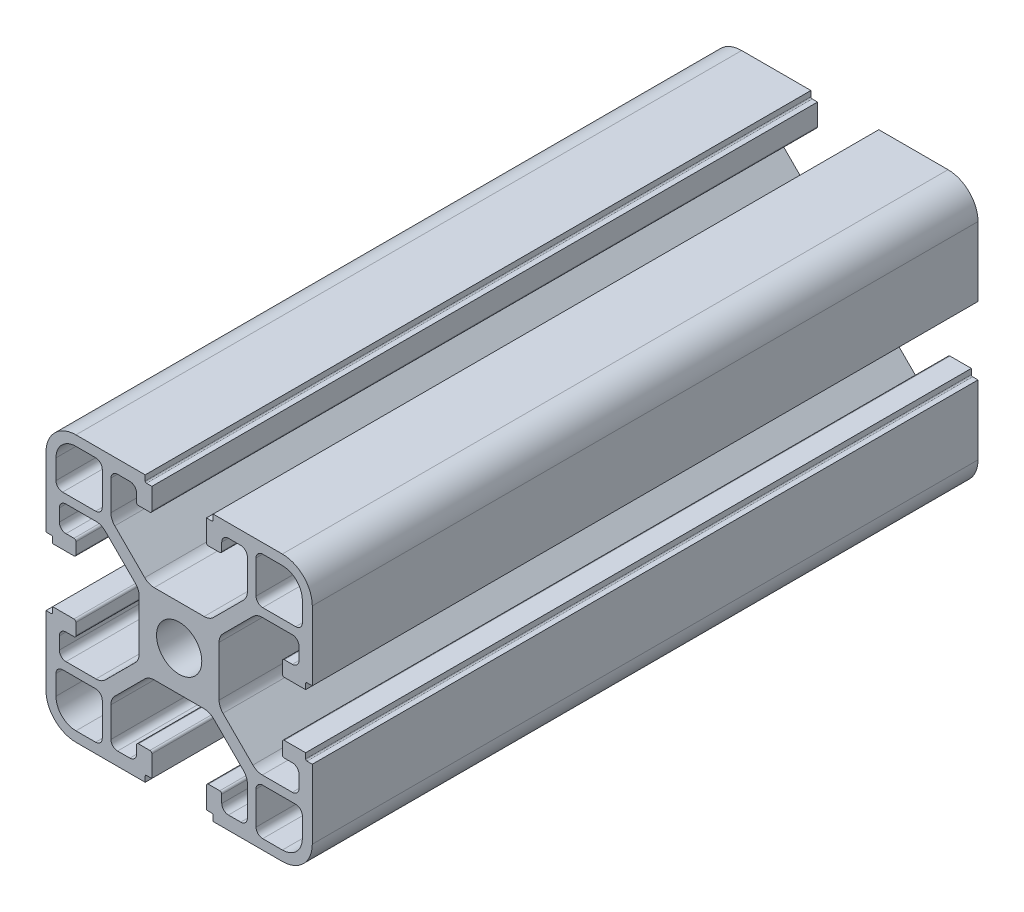
SolidWorks part; units mm, degrees
ref_plane "前视基准面" through (0, 0, 0) normal (0, 0, 1) x (1, 0, 0)
ref_plane "上视基准面" through (0, 0, 0) normal (0, 1, 0) x (1, 0, 0)
ref_plane "右视基准面" through (0, 0, 0) normal (1, 0, 0) x (0, 0, -1)
sketch "草图1" plane through (0, 0, 0) normal (0, 0, 1) x (1, 0, 0)
  line L0 (-6.6936, 20.4455) -> (-17.0936, 20.4455)
  line L1 (-21.5936, 15.9455) -> (-21.5936, 5.5455)
  line L2 (-5.6936, 19.4455) -> (-6.4936, 19.4455)
  line L3 (-6.6936, 19.6455) -> (-6.6936, 20.4455)
  line L4 (-21.5936, 5.5455) -> (-20.7936, 5.5455)
  line L5 (-20.5936, 5.3455) -> (-20.5936, 4.5455)
  line L6 (-14.0863, 10.6955) -> (-18.5936, 10.6955)
  line L7 (-19.5936, 9.6955) -> (-19.5936, 7.8455)
  line L8 (-18.5936, 6.8455) -> (-17.3936, 6.8455)
  line L9 (-17.0936, 6.5455) -> (-17.0936, 4.8455)
  line L10 (-17.3936, 4.5455) -> (-20.5936, 4.5455)
  line L11 (-5.6936, 19.4455) -> (-5.6936, 16.2455)
  line L12 (-5.9936, 15.9455) -> (-7.6936, 15.9455)
  line L13 (-7.9936, 16.2455) -> (-7.9936, 17.4455)
  line L14 (-8.9936, 18.4455) -> (-10.8436, 18.4455)
  line L15 (-11.8436, 17.4455) -> (-11.8436, 12.9381)
  line L16 (-11.2578, 11.5239) -> (-6.7652, 7.0312)
  line L17 (-5.351, 6.4455) -> (2.1637, 6.4455)
  line L18 (4.4064, 4.2028) -> (4.4064, -3.3119)
  line L19 (2.1637, -5.5545) -> (-5.351, -5.5545)
  line L20 (-7.5936, -3.3119) -> (-7.5936, 4.2028)
  line L21 (-8.1794, 5.617) -> (-12.6721, 10.1097)
  line L22 (-20.0976, 15.9495) -> (-20.0976, 12.9955)
  line L23 (-19.0976, 11.9955) -> (-14.1436, 11.9955)
  line L24 (-13.1436, 12.9955) -> (-13.1436, 17.9495)
  line L25 (-14.1436, 18.9495) -> (-17.0976, 18.9495)
  line L26 (3.5064, 20.4455) -> (13.9064, 20.4455)
  line L27 (18.4064, 15.9455) -> (18.4064, 5.5455)
  line L28 (2.5064, 19.4455) -> (3.3064, 19.4455)
  line L29 (3.5064, 19.6455) -> (3.5064, 20.4455)
  line L30 (18.4064, 5.5455) -> (17.6064, 5.5455)
  line L31 (17.4064, 5.3455) -> (17.4064, 4.5455)
  line L32 (10.899, 10.6955) -> (15.4064, 10.6955)
  line L33 (16.4064, 9.6955) -> (16.4064, 7.8455)
  line L34 (15.4064, 6.8455) -> (14.2064, 6.8455)
  line L35 (13.9064, 6.5455) -> (13.9064, 4.8455)
  line L36 (14.2064, 4.5455) -> (17.4064, 4.5455)
  line L37 (2.5064, 19.4455) -> (2.5064, 16.2455)
  line L38 (2.8064, 15.9455) -> (4.5064, 15.9455)
  line L39 (4.8064, 16.2455) -> (4.8064, 17.4455)
  line L40 (5.8064, 18.4455) -> (7.6564, 18.4455)
  line L41 (8.6564, 17.4455) -> (8.6564, 12.9381)
  line L42 (8.0706, 11.5239) -> (3.5779, 7.0312)
  line L43 (4.9922, 5.617) -> (9.4848, 10.1097)
  line L44 (16.9104, 15.9495) -> (16.9104, 12.9955)
  line L45 (15.9104, 11.9955) -> (10.9564, 11.9955)
  line L46 (9.9564, 12.9955) -> (9.9564, 17.9495)
  line L47 (10.9564, 18.9495) -> (13.9104, 18.9495)
  line L48 (-6.6936, -19.5545) -> (-17.0936, -19.5545)
  line L49 (-21.5936, -15.0545) -> (-21.5936, -4.6545)
  line L50 (-5.6936, -18.5545) -> (-6.4936, -18.5545)
  line L51 (-6.6936, -18.7545) -> (-6.6936, -19.5545)
  line L52 (-21.5936, -4.6545) -> (-20.7936, -4.6545)
  line L53 (-20.5936, -4.4545) -> (-20.5936, -3.6545)
  line L54 (-14.0863, -9.8045) -> (-18.5936, -9.8045)
  line L55 (-19.5936, -8.8045) -> (-19.5936, -6.9545)
  line L56 (-18.5936, -5.9545) -> (-17.3936, -5.9545)
  line L57 (-17.0936, -5.6545) -> (-17.0936, -3.9545)
  line L58 (-17.3936, -3.6545) -> (-20.5936, -3.6545)
  line L59 (-5.6936, -18.5545) -> (-5.6936, -15.3545)
  line L60 (-5.9936, -15.0545) -> (-7.6936, -15.0545)
  line L61 (-7.9936, -15.3545) -> (-7.9936, -16.5545)
  line L62 (-8.9936, -17.5545) -> (-10.8436, -17.5545)
  line L63 (-11.8436, -16.5545) -> (-11.8436, -12.0472)
  line L64 (-11.2578, -10.633) -> (-6.7652, -6.1403)
  line L65 (-8.1794, -4.7261) -> (-12.6721, -9.2188)
  line L66 (-20.0976, -15.0585) -> (-20.0976, -12.1045)
  line L67 (-19.0976, -11.1045) -> (-14.1436, -11.1045)
  line L68 (-13.1436, -12.1045) -> (-13.1436, -17.0585)
  line L69 (-14.1436, -18.0585) -> (-17.0976, -18.0585)
  line L70 (3.5064, -19.5545) -> (13.9064, -19.5545)
  line L71 (18.4064, -15.0545) -> (18.4064, -4.6545)
  line L72 (2.5064, -18.5545) -> (3.3064, -18.5545)
  line L73 (3.5064, -18.7545) -> (3.5064, -19.5545)
  line L74 (18.4064, -4.6545) -> (17.6064, -4.6545)
  line L75 (17.4064, -4.4545) -> (17.4064, -3.6545)
  line L76 (10.899, -9.8045) -> (15.4064, -9.8045)
  line L77 (16.4064, -8.8045) -> (16.4064, -6.9545)
  line L78 (15.4064, -5.9545) -> (14.2064, -5.9545)
  line L79 (13.9064, -5.6545) -> (13.9064, -3.9545)
  line L80 (14.2064, -3.6545) -> (17.4064, -3.6545)
  line L81 (2.5064, -18.5545) -> (2.5064, -15.3545)
  line L82 (2.8064, -15.0545) -> (4.5064, -15.0545)
  line L83 (4.8064, -15.3545) -> (4.8064, -16.5545)
  line L84 (5.8064, -17.5545) -> (7.6564, -17.5545)
  line L85 (8.6564, -16.5545) -> (8.6564, -12.0472)
  line L86 (8.0706, -10.633) -> (3.5779, -6.1403)
  line L87 (4.9922, -4.7261) -> (9.4848, -9.2188)
  line L88 (16.9104, -15.0585) -> (16.9104, -12.1045)
  line L89 (15.9104, -11.1045) -> (10.9564, -11.1045)
  line L90 (9.9564, -12.1045) -> (9.9564, -17.0585)
  line L91 (10.9564, -18.0585) -> (13.9104, -18.0585)
  arc A0 (-17.0936, 20.4455) -> (-21.5936, 15.9455) centre (-17.0936, 15.9455) ccw
  arc A1 (-6.6936, 19.6455) -> (-6.4936, 19.4455) centre (-6.4936, 19.6455) ccw
  arc A2 (-20.5936, 5.3455) -> (-20.7936, 5.5455) centre (-20.7936, 5.3455) ccw
  arc A3 (-18.5936, 10.6955) -> (-19.5936, 9.6955) centre (-18.5936, 9.6955) ccw
  arc A4 (-19.5936, 7.8455) -> (-18.5936, 6.8455) centre (-18.5936, 7.8455) ccw
  arc A5 (-17.0936, 6.5455) -> (-17.3936, 6.8455) centre (-17.3936, 6.5455) ccw
  arc A6 (-17.3936, 4.5455) -> (-17.0936, 4.8455) centre (-17.3936, 4.8455) ccw
  arc A7 (-5.9936, 15.9455) -> (-5.6936, 16.2455) centre (-5.9936, 16.2455) ccw
  arc A8 (-7.9936, 16.2455) -> (-7.6936, 15.9455) centre (-7.6936, 16.2455) ccw
  arc A9 (-7.9936, 17.4455) -> (-8.9936, 18.4455) centre (-8.9936, 17.4455) ccw
  arc A10 (-10.8436, 18.4455) -> (-11.8436, 17.4455) centre (-10.8436, 17.4455) ccw
  arc A11 (-11.8436, 12.9381) -> (-11.2578, 11.5239) centre (-9.8436, 12.9381) ccw
  arc A12 (-6.7652, 7.0312) -> (-5.351, 6.4455) centre (-5.351, 8.4455) ccw
  arc A13 (-7.5936, 4.2028) -> (-8.1794, 5.617) centre (-9.5936, 4.2028) ccw
  circle A14 centre (-1.5936, 0.4455) radius 3.4
  arc A15 (-12.6721, 10.1097) -> (-14.0863, 10.6955) centre (-14.0863, 8.6955) ccw
  arc A16 (-20.0976, 12.9955) -> (-19.0976, 11.9955) centre (-19.0976, 12.9955) ccw
  arc A17 (-14.1436, 11.9955) -> (-13.1436, 12.9955) centre (-14.1436, 12.9955) ccw
  arc A18 (-13.1436, 17.9495) -> (-14.1436, 18.9495) centre (-14.1436, 17.9495) ccw
  arc A19 (-17.0976, 18.9495) -> (-20.0976, 15.9495) centre (-17.0976, 15.9495) ccw
  arc A20 (18.4064, 15.9455) -> (13.9064, 20.4455) centre (13.9064, 15.9455) ccw
  arc A21 (3.3064, 19.4455) -> (3.5064, 19.6455) centre (3.3064, 19.6455) ccw
  arc A22 (17.6064, 5.5455) -> (17.4064, 5.3455) centre (17.6064, 5.3455) ccw
  arc A23 (16.4064, 9.6955) -> (15.4064, 10.6955) centre (15.4064, 9.6955) ccw
  arc A24 (15.4064, 6.8455) -> (16.4064, 7.8455) centre (15.4064, 7.8455) ccw
  arc A25 (14.2064, 6.8455) -> (13.9064, 6.5455) centre (14.2064, 6.5455) ccw
  arc A26 (13.9064, 4.8455) -> (14.2064, 4.5455) centre (14.2064, 4.8455) ccw
  arc A27 (2.5064, 16.2455) -> (2.8064, 15.9455) centre (2.8064, 16.2455) ccw
  arc A28 (4.5064, 15.9455) -> (4.8064, 16.2455) centre (4.5064, 16.2455) ccw
  arc A29 (5.8064, 18.4455) -> (4.8064, 17.4455) centre (5.8064, 17.4455) ccw
  arc A30 (8.6564, 17.4455) -> (7.6564, 18.4455) centre (7.6564, 17.4455) ccw
  arc A31 (8.0706, 11.5239) -> (8.6564, 12.9381) centre (6.6564, 12.9381) ccw
  arc A32 (2.1637, 6.4455) -> (3.5779, 7.0312) centre (2.1637, 8.4455) ccw
  arc A33 (4.9922, 5.617) -> (4.4064, 4.2028) centre (6.4064, 4.2028) ccw
  arc A34 (10.899, 10.6955) -> (9.4848, 10.1097) centre (10.899, 8.6955) ccw
  arc A35 (15.9104, 11.9955) -> (16.9104, 12.9955) centre (15.9104, 12.9955) ccw
  arc A36 (9.9564, 12.9955) -> (10.9564, 11.9955) centre (10.9564, 12.9955) ccw
  arc A37 (10.9564, 18.9495) -> (9.9564, 17.9495) centre (10.9564, 17.9495) ccw
  arc A38 (16.9104, 15.9495) -> (13.9104, 18.9495) centre (13.9104, 15.9495) ccw
  arc A39 (-21.5936, -15.0545) -> (-17.0936, -19.5545) centre (-17.0936, -15.0545) ccw
  arc A40 (-6.4936, -18.5545) -> (-6.6936, -18.7545) centre (-6.4936, -18.7545) ccw
  arc A41 (-20.7936, -4.6545) -> (-20.5936, -4.4545) centre (-20.7936, -4.4545) ccw
  arc A42 (-19.5936, -8.8045) -> (-18.5936, -9.8045) centre (-18.5936, -8.8045) ccw
  arc A43 (-18.5936, -5.9545) -> (-19.5936, -6.9545) centre (-18.5936, -6.9545) ccw
  arc A44 (-17.3936, -5.9545) -> (-17.0936, -5.6545) centre (-17.3936, -5.6545) ccw
  arc A45 (-17.0936, -3.9545) -> (-17.3936, -3.6545) centre (-17.3936, -3.9545) ccw
  arc A46 (-5.6936, -15.3545) -> (-5.9936, -15.0545) centre (-5.9936, -15.3545) ccw
  arc A47 (-7.6936, -15.0545) -> (-7.9936, -15.3545) centre (-7.6936, -15.3545) ccw
  arc A48 (-8.9936, -17.5545) -> (-7.9936, -16.5545) centre (-8.9936, -16.5545) ccw
  arc A49 (-11.8436, -16.5545) -> (-10.8436, -17.5545) centre (-10.8436, -16.5545) ccw
  arc A50 (-11.2578, -10.633) -> (-11.8436, -12.0472) centre (-9.8436, -12.0472) ccw
  arc A51 (-5.351, -5.5545) -> (-6.7652, -6.1403) centre (-5.351, -7.5545) ccw
  arc A52 (-8.1794, -4.7261) -> (-7.5936, -3.3119) centre (-9.5936, -3.3119) ccw
  arc A53 (-14.0863, -9.8045) -> (-12.6721, -9.2188) centre (-14.0863, -7.8045) ccw
  arc A54 (-19.0976, -11.1045) -> (-20.0976, -12.1045) centre (-19.0976, -12.1045) ccw
  arc A55 (-13.1436, -12.1045) -> (-14.1436, -11.1045) centre (-14.1436, -12.1045) ccw
  arc A56 (-14.1436, -18.0585) -> (-13.1436, -17.0585) centre (-14.1436, -17.0585) ccw
  arc A57 (-20.0976, -15.0585) -> (-17.0976, -18.0585) centre (-17.0976, -15.0585) ccw
  arc A58 (13.9064, -19.5545) -> (18.4064, -15.0545) centre (13.9064, -15.0545) ccw
  arc A59 (3.5064, -18.7545) -> (3.3064, -18.5545) centre (3.3064, -18.7545) ccw
  arc A60 (17.4064, -4.4545) -> (17.6064, -4.6545) centre (17.6064, -4.4545) ccw
  arc A61 (15.4064, -9.8045) -> (16.4064, -8.8045) centre (15.4064, -8.8045) ccw
  arc A62 (16.4064, -6.9545) -> (15.4064, -5.9545) centre (15.4064, -6.9545) ccw
  arc A63 (13.9064, -5.6545) -> (14.2064, -5.9545) centre (14.2064, -5.6545) ccw
  arc A64 (14.2064, -3.6545) -> (13.9064, -3.9545) centre (14.2064, -3.9545) ccw
  arc A65 (2.8064, -15.0545) -> (2.5064, -15.3545) centre (2.8064, -15.3545) ccw
  arc A66 (4.8064, -15.3545) -> (4.5064, -15.0545) centre (4.5064, -15.3545) ccw
  arc A67 (4.8064, -16.5545) -> (5.8064, -17.5545) centre (5.8064, -16.5545) ccw
  arc A68 (7.6564, -17.5545) -> (8.6564, -16.5545) centre (7.6564, -16.5545) ccw
  arc A69 (8.6564, -12.0472) -> (8.0706, -10.633) centre (6.6564, -12.0472) ccw
  arc A70 (3.5779, -6.1403) -> (2.1637, -5.5545) centre (2.1637, -7.5545) ccw
  arc A71 (4.4064, -3.3119) -> (4.9922, -4.7261) centre (6.4064, -3.3119) ccw
  arc A72 (9.4848, -9.2188) -> (10.899, -9.8045) centre (10.899, -7.8045) ccw
  arc A73 (16.9104, -12.1045) -> (15.9104, -11.1045) centre (15.9104, -12.1045) ccw
  arc A74 (10.9564, -11.1045) -> (9.9564, -12.1045) centre (10.9564, -12.1045) ccw
  arc A75 (9.9564, -17.0585) -> (10.9564, -18.0585) centre (10.9564, -17.0585) ccw
  arc A76 (13.9104, -18.0585) -> (16.9104, -15.0585) centre (13.9104, -15.0585) ccw
extrude "凸台-拉伸1" add sketch "草图1" along normal blind 100
